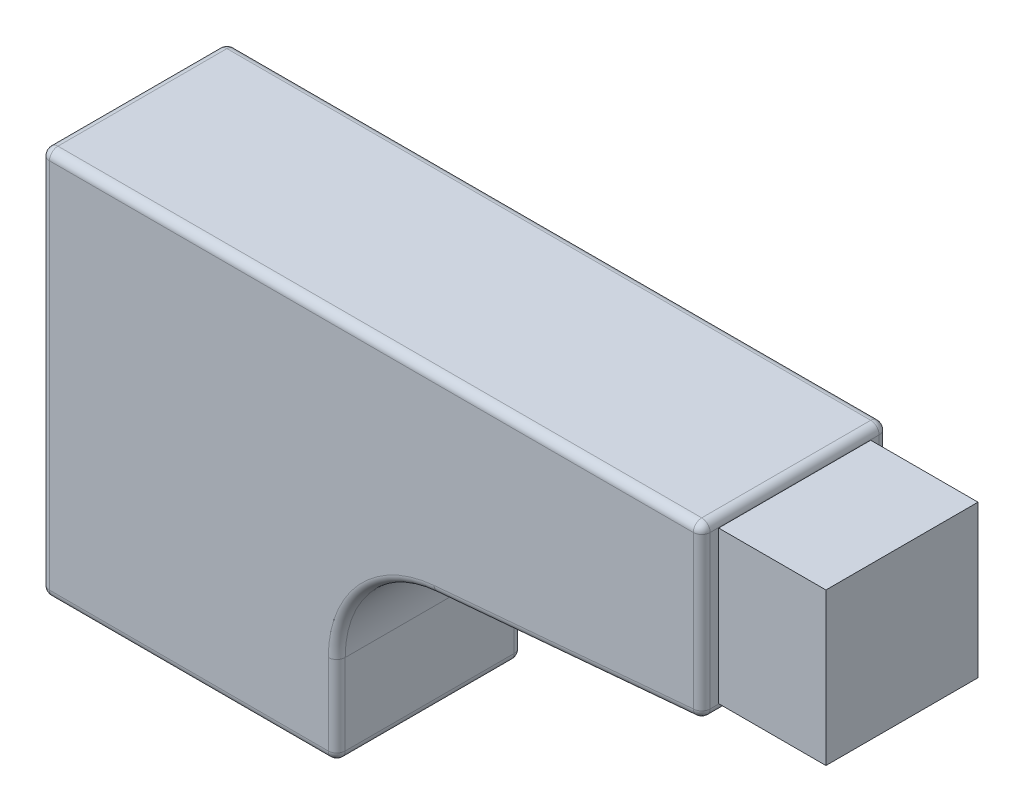
SolidWorks part; units mm, degrees
material "Aluminum Red Anodize"
ref_plane "Front" through (0, 0, 0) normal (0, 0, 1) x (1, 0, 0)
ref_plane "Top" through (0, 0, 0) normal (0, 1, 0) x (1, 0, 0)
ref_plane "Right" through (0, 0, 0) normal (1, 0, 0) x (0, 0, -1)
sketch "Sketch1" plane through (0, 0, 0) normal (0, 0, 1) x (1, 0, 0)
  line L0 (-19.55, -11.5) -> (19.55, 11.5) construction
  line L1 (-19.55, 11.5) -> (19.55, 11.5)
  line L2 (-19.55, 11.5) -> (-19.55, -11.5)
  line L3 (-19.55, -11.5) -> (19.55, -11.5)
  line L4 (19.55, 11.5) -> (19.55, -11.5)
  dimension "D1" = 39.1
  dimension "D2" = 23
extrude "Boss-Extrude1" add sketch "Sketch1" along normal mid plane 11
sketch "Sketch2" plane through (0, 0, 5.5) normal (0, 0, 1) x (1, 0, 0)
  line L0 (-19.55, 11.5) -> (-19.55, -11.5) construction
  line L1 (19.55, -11.5) -> (-2.05, -11.5)
  line L2 (19.55, -11.5) -> (19.55, 1.5)
  line L3 (19.55, 1.5) -> (-2.05, -0.3898)
  line L4 (-2.05, -11.5) -> (-2.05, -0.3898)
  line L5 (19.55, 11.5) -> (-19.55, 11.5) construction
  dimension "D1" = 17.5
  dimension "D2" = 11.1102
  dimension "D3" = 10
  dimension "D4" = 5
extrude "Cut-Extrude1" cut sketch "Sketch2" against normal through all
fillet "Fillet1" radius 6.35 1 edges at (-2.05, -0.3898, 0)
fillet "Fillet2" radius 0.5 19 edges at (19.55, 6.5, -5.5) (19.55, 6.5, 5.5) (-19.55, 0, -5.5) (-19.55, 0, 5.5) (-2.05, -8.8542, -5.5) (-0.3817, -1.9185, -5.5) (-2.05, -8.8542, 5.5) (-0.3817, -1.9185, 5.5) (-10.8, -11.5, -5.5) (-2.05, -11.5, 0) (-19.55, -11.5, 0) (-10.8, -11.5, 5.5) (11.6483, 0.8087, -5.5) (11.6483, 0.8087, 5.5) (19.55, 1.5, 0) (19.55, 11.5, 0) (0, 11.5, -5.5) (-19.55, 11.5, 0) (0, 11.5, 5.5)
sketch "Sketch3" plane through (19.55, 0, 0) normal (1, 0, 0) x (0, 0, -1)
  line L0 (5, 1.9582) -> (5, 11) construction
  line L1 (-4.5, 10.9791) -> (4.5, 10.9791)
  line L2 (-4.5, 10.9791) -> (-4.5, 1.9791)
  line L3 (-4.5, 1.9791) -> (4.5, 1.9791)
  line L4 (4.5, 10.9791) -> (4.5, 1.9791)
  line L5 (-4.5, 10.9791) -> (4.5, 1.9791) construction
  line L6 (-4.5, 1.9791) -> (4.5, 10.9791) construction
  point P0 (0, 6.4791)
  point P8 (5, 6.4791)
  dimension "D1" = 9
extrude "Boss-Extrude2" add sketch "Sketch3" along normal blind 6.35
